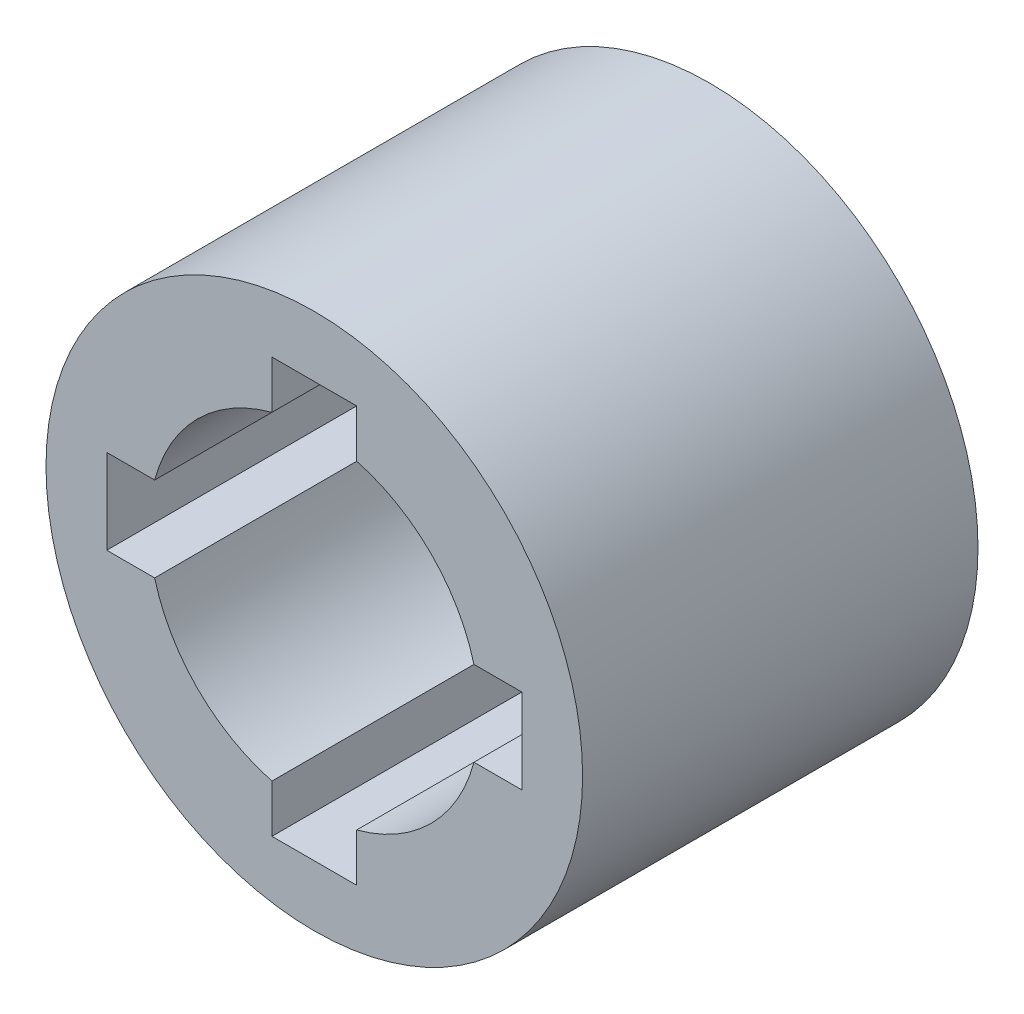
SolidWorks part; units mm, degrees
ref_plane "Front Plane" through (0, 0, 0) normal (0, 0, 1) x (1, 0, 0)
ref_plane "Top Plane" through (0, 0, 0) normal (0, 1, 0) x (1, 0, 0)
ref_plane "Right Plane" through (0, 0, 0) normal (1, 0, 0) x (0, 0, -1)
sketch "Sketch1" plane through (0, 0, 0) normal (0, 0, 1) x (1, 0, 0)
  line L0 (-1.5, 5.6528) -> (-1.5, 7.3485)
  line L1 (-1.5, 4.3485) -> (1.5, 4.3485) construction
  line L2 (-1.5, 4.3485) -> (-1.5, 7.3485) construction
  line L3 (-1.5, 7.3485) -> (1.5, 7.3485) construction
  line L4 (1.5, 4.3485) -> (1.5, 7.3485) construction
  line L5 (-1.5, 4.3485) -> (1.5, 7.3485) construction
  line L6 (-1.5, 7.3485) -> (1.5, 4.3485) construction
  line L7 (4.3485, -1.5) -> (7.3485, -1.5) construction
  line L8 (4.3485, -1.5) -> (4.3485, 1.5) construction
  line L9 (4.3485, 1.5) -> (7.3485, 1.5) construction
  line L10 (7.3485, -1.5) -> (7.3485, 1.5) construction
  line L11 (4.3485, -1.5) -> (7.3485, 1.5) construction
  line L12 (4.3485, 1.5) -> (7.3485, -1.5) construction
  line L13 (-1.5, -7.3485) -> (1.5, -7.3485) construction
  line L14 (-1.5, -7.3485) -> (-1.5, -4.3485) construction
  line L15 (-1.5, -4.3485) -> (1.5, -4.3485) construction
  line L16 (1.5, -7.3485) -> (1.5, -4.3485) construction
  line L17 (-1.5, -7.3485) -> (1.5, -4.3485) construction
  line L18 (-1.5, -4.3485) -> (1.5, -7.3485) construction
  line L19 (-7.3485, -1.5) -> (-4.3485, -1.5) construction
  line L20 (-7.3485, -1.5) -> (-7.3485, 1.5) construction
  line L21 (-7.3485, 1.5) -> (-4.3485, 1.5) construction
  line L22 (-4.3485, -1.5) -> (-4.3485, 1.5) construction
  line L23 (-7.3485, -1.5) -> (-4.3485, 1.5) construction
  line L24 (-7.3485, 1.5) -> (-4.3485, -1.5) construction
  line L25 (-1.5, 7.3485) -> (1.5, 7.3485)
  line L26 (1.5, 7.3485) -> (1.5, 5.6528)
  line L27 (5.6528, 1.5) -> (7.3485, 1.5)
  line L28 (7.3485, 1.5) -> (7.3485, -1.5)
  line L29 (7.3485, -1.5) -> (5.6528, -1.5)
  line L30 (1.5, -5.6528) -> (1.5, -7.3485)
  line L31 (1.5, -7.3485) -> (-1.5, -7.3485)
  line L32 (-1.5, -7.3485) -> (-1.5, -5.6528)
  line L33 (-5.6528, -1.5) -> (-7.3485, -1.5)
  line L34 (-7.3485, -1.5) -> (-7.3485, 1.5)
  line L35 (-7.3485, 1.5) -> (-5.6528, 1.5)
  circle A0 centre (0, 0) radius 9.5
  circle A1 centre (0, 0) radius 7.5 construction
  arc A2 (-1.5, 5.6528) -> (-5.6528, 1.5) centre (0, 0) ccw
  arc A3 (5.6528, 1.5) -> (1.5, 5.6528) centre (0, 0) ccw
  arc A4 (1.5, -5.6528) -> (5.6528, -1.5) centre (0, 0) ccw
  arc A5 (-5.6528, -1.5) -> (-1.5, -5.6528) centre (0, 0) ccw
  point P5 (0, 5.8485)
  point P10 (5.8485, 0)
  point P15 (0, -5.8485)
  point P20 (-5.8485, 0)
  point P25 (-1.5, 5.6528)
  point P26 (1.5, 5.6528)
  point P27 (5.6528, 1.5)
  point P28 (5.6528, -1.5)
  point P29 (1.5, -5.6528)
  point P31 (-5.6528, -1.5)
  point P32 (-5.6528, 1.5)
  dimension "D1" = 15
  dimension "D3" = 19
  dimension "D2" = 3
extrude "Boss-Extrude1" add sketch "Sketch1" along normal blind 14
